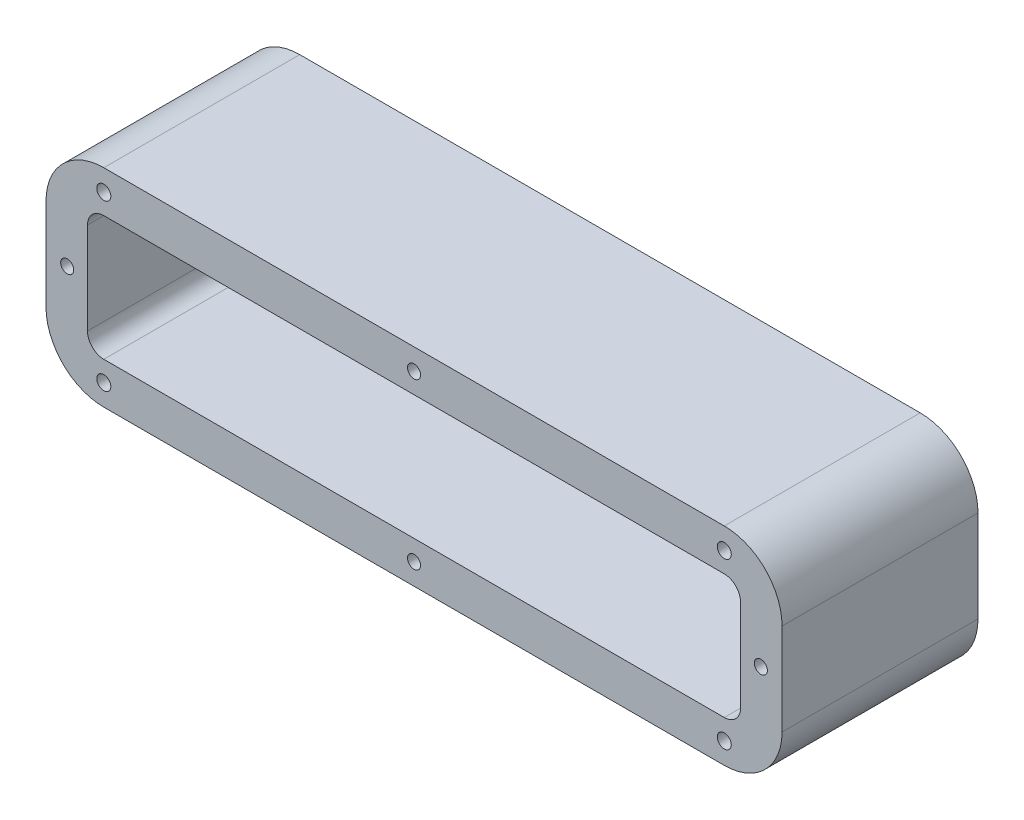
SolidWorks part; units mm, degrees
ref_plane "Plan de face" through (0, 0, 0) normal (0, 0, 1) x (1, 0, 0)
ref_plane "Plan de dessus" through (0, 0, 0) normal (0, 1, 0) x (1, 0, 0)
ref_plane "Plan de droite" through (0, 0, 0) normal (1, 0, 0) x (0, 0, -1)
sketch "Esquisse1" plane through (0, 0, 0) normal (0, 0, 1) x (1, 0, 0)
  line L0 (0, 0) -> (-106.2, 0) construction
  line L1 (-95, -31.75) -> (95, -31.75)
  line L2 (-112.7, -14.05) -> (-112.7, 14.05)
  line L3 (-95, 31.75) -> (95, 31.75)
  line L4 (112.7, -14.05) -> (112.7, 14.05)
  line L5 (-112.7, -31.75) -> (112.7, 31.75) construction
  line L6 (-112.7, 31.75) -> (112.7, -31.75) construction
  line L7 (-95, -19.05) -> (95, -19.05)
  line L8 (-100, -14.05) -> (-100, 14.05)
  line L9 (-95, 19.05) -> (95, 19.05)
  line L10 (100, -14.05) -> (100, 14.05)
  line L11 (-100, -19.05) -> (100, 19.05) construction
  line L12 (-100, 19.05) -> (100, -19.05) construction
  line L13 (0, 0) -> (0, -25.25) construction
  arc A0 (95, 31.75) -> (112.7, 14.05) centre (95, 14.05) cw
  arc A1 (95, -31.75) -> (112.7, -14.05) centre (95, -14.05) ccw
  arc A2 (-95, -31.75) -> (-112.7, -14.05) centre (-95, -14.05) cw
  arc A3 (-112.7, 14.05) -> (-95, 31.75) centre (-95, 14.05) cw
  arc A4 (95, 19.05) -> (100, 14.05) centre (95, 14.05) cw
  arc A5 (95, -19.05) -> (100, -14.05) centre (95, -14.05) ccw
  arc A6 (-95, -19.05) -> (-100, -14.05) centre (-95, -14.05) cw
  arc A7 (-100, 14.05) -> (-95, 19.05) centre (-95, 14.05) cw
  circle A8 centre (-106.2, 0) radius 2
  circle A9 centre (0, 25.25) radius 2
  circle A10 centre (-95, 25.25) radius 2.1469
  circle A11 centre (-95, -25.25) radius 2.1469
  circle A12 centre (0, -25.25) radius 2
  circle A13 centre (95, -25.25) radius 2.1469
  circle A14 centre (106.2, 0) radius 2
  circle A15 centre (95, 25.25) radius 2.1469
  point P0 (0, 0)
  point P18 (0, 0)
  dimension "D3" = 17.7
  dimension "D6" = 5
  dimension "D8" = 4
  dimension "D10" = 4
  dimension "D1" = 225.4
  dimension "D2" = 63.5
  dimension "D4" = 200
  dimension "D5" = 38.1
  dimension "D7" = 6.5
  dimension "D9" = 6.5
  dimension "D11" = 95
  dimension "D12" = 6.5
extrude "Boss.-Extru.1" add sketch "Esquisse1" along normal blind 60
